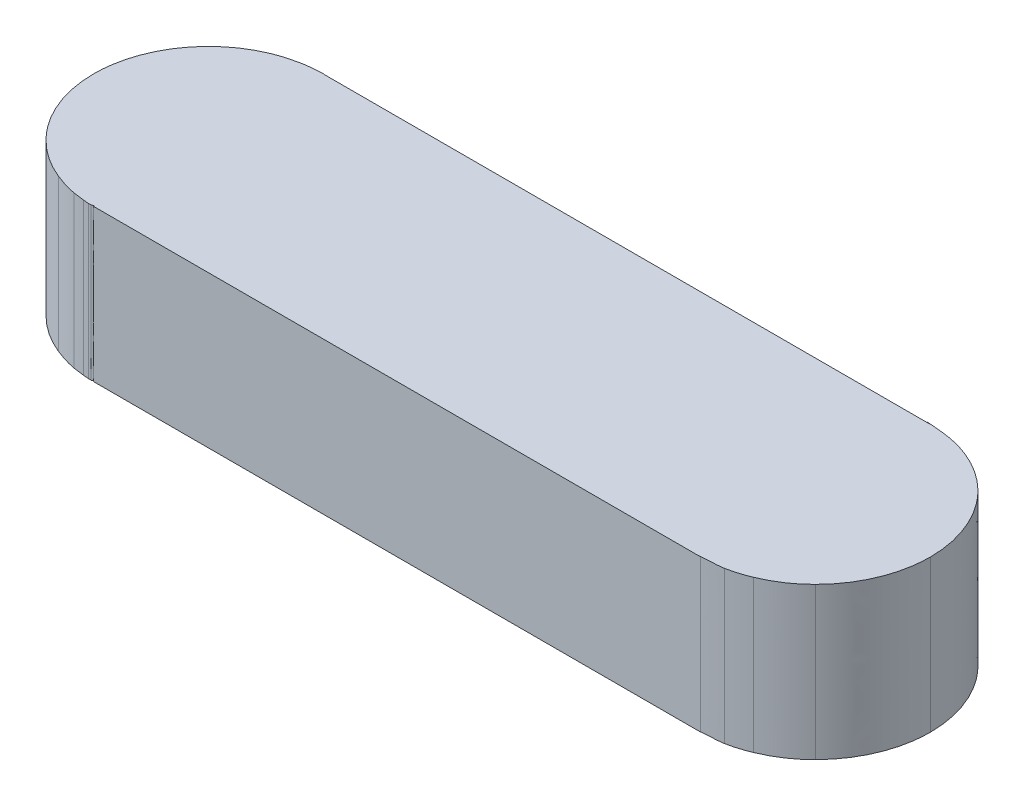
SolidWorks part; units mm, degrees
ref_plane "Front Plane" through (0, 0, 0) normal (0, 0, 1) x (1, 0, 0)
ref_plane "Top Plane" through (0, 0, 0) normal (0, 1, 0) x (1, 0, 0)
ref_plane "Right Plane" through (0, 0, 0) normal (1, 0, 0) x (0, 0, -1)
sketch "Sketch1" plane through (0, 0, 0) normal (0, 1, 0) x (1, 0, 0)
  line L0 (5.023, 0.2205) -> (30.4202, 0.2205)
  line L1 (30.4202, 9.8251) -> (5.023, 9.824)
  spline S0 degree 3 poles (5.023, 9.824) (5.0919, 9.844) (4.9471, 9.824) (4.9127, 9.824) knots 0 0 0 0 1 1 1 1
  spline S1 degree 3 poles (4.9127, 9.824) (4.8782, 9.824) (4.8369, 9.819) (4.8025, 9.819) knots 0 0 0 0 1 1 1 1
  spline S2 degree 3 poles (4.8025, 9.819) (4.7266, 9.819) (4.651, 9.8141) (4.5751, 9.804) knots 0 0 0 0 1 1 1 1
  spline S3 degree 3 poles (4.5751, 9.804) (4.4167, 9.789) (4.265, 9.769) (4.1135, 9.735) knots 0 0 0 0 1 1 1 1
  spline S4 degree 3 poles (4.1135, 9.735) (3.7965, 9.673) (3.4865, 9.5835) (3.1833, 9.4595) knots 0 0 0 0 1 1 1 1
  spline S5 degree 3 poles (3.1833, 9.4595) (2.5838, 9.2115) (2.0877, 8.8739) (1.6261, 8.4191) knots 0 0 0 0 1 1 1 1
  spline S6 degree 3 poles (1.6261, 8.4191) (0.7235, 7.5165) (0.2205, 6.2969) (0.2205, 5.0222) knots 0 0 0 0 1 1 1 1
  spline S7 degree 3 poles (0.2205, 5.0222) (0.2205, 3.7476) (0.7235, 2.528) (1.6261, 1.6254) knots 0 0 0 0 1 1 1 1
  spline S8 degree 3 poles (1.6261, 1.6254) (2.0878, 1.1639) (2.5838, 0.833) (3.1833, 0.585) knots 0 0 0 0 1 1 1 1
  spline S9 degree 3 poles (3.1833, 0.585) (3.4865, 0.461) (3.7965, 0.3645) (4.1135, 0.3025) knots 0 0 0 0 1 1 1 1
  spline S10 degree 3 poles (4.1135, 0.3025) (4.2649, 0.2775) (4.4166, 0.2525) (4.5751, 0.2405) knots 0 0 0 0 1 1 1 1
  spline S11 degree 3 poles (4.5751, 0.2405) (4.6509, 0.2355) (4.7266, 0.2255) (4.8025, 0.2205) knots 0 0 0 0 1 1 1 1
  spline S12 degree 3 poles (4.8025, 0.2205) (4.837, 0.2205) (4.8783, 0.2205) (4.9127, 0.2205) knots 0 0 0 0 1 1 1 1
  spline S13 degree 3 poles (4.9127, 0.2205) (4.9472, 0.2205) (5.023, 0.2895) (5.023, 0.2205) knots 0 0 0 0 1 1 1 1
  spline S14 degree 3 poles (30.4202, 0.2205) (29.8139, 0.2205) (31.0335, 0.2455) (31.3297, 0.303) knots 0 0 0 0 1 1 1 1
  spline S15 degree 3 poles (31.3297, 0.303) (31.6536, 0.365) (31.9636, 0.4615) (32.2599, 0.5855) knots 0 0 0 0 1 1 1 1
  spline S16 degree 3 poles (32.2599, 0.5855) (32.8594, 0.8335) (33.3623, 1.1642) (33.8171, 1.6259) knots 0 0 0 0 1 1 1 1
  spline S17 degree 3 poles (33.8171, 1.6259) (34.7197, 2.5216) (35.2296, 3.7481) (35.2296, 5.0227) knots 0 0 0 0 1 1 1 1
  spline S18 degree 3 poles (35.2296, 5.0227) (35.2296, 6.2974) (34.7197, 7.517) (33.824, 8.4196) knots 0 0 0 0 1 1 1 1
  spline S19 degree 3 poles (33.824, 8.4196) (33.3623, 8.8746) (32.8594, 9.212) (32.2599, 9.4601) knots 0 0 0 0 1 1 1 1
  spline S20 degree 3 poles (32.2599, 9.4601) (31.9637, 9.584) (31.6536, 9.6735) (31.3297, 9.7355) knots 0 0 0 0 1 1 1 1
  spline S21 degree 3 poles (31.3297, 9.7355) (31.0334, 9.7975) (29.8208, 9.894) (30.4202, 9.8251) knots 0 0 0 0 1 1 1 1
extrude "Boss-Extrude1" add sketch "Sketch1" along normal blind 6.35
sketch "Sketch2" plane through (0, 6.35, 0) normal (0, 1, 0) x (1, 0, 0)
  line L0 (30.4202, 9.8251) -> (5.023, 9.824) construction
  line L1 (5.023, 0.2205) -> (30.4202, 0.2205) construction
  line L2 (5.0223, 5.0223) -> (30.4273, 5.0228) construction
  circle A0 centre (5.0223, 5.0223) radius 4.8018
  circle A1 centre (30.4273, 5.0228) radius 4.8023
